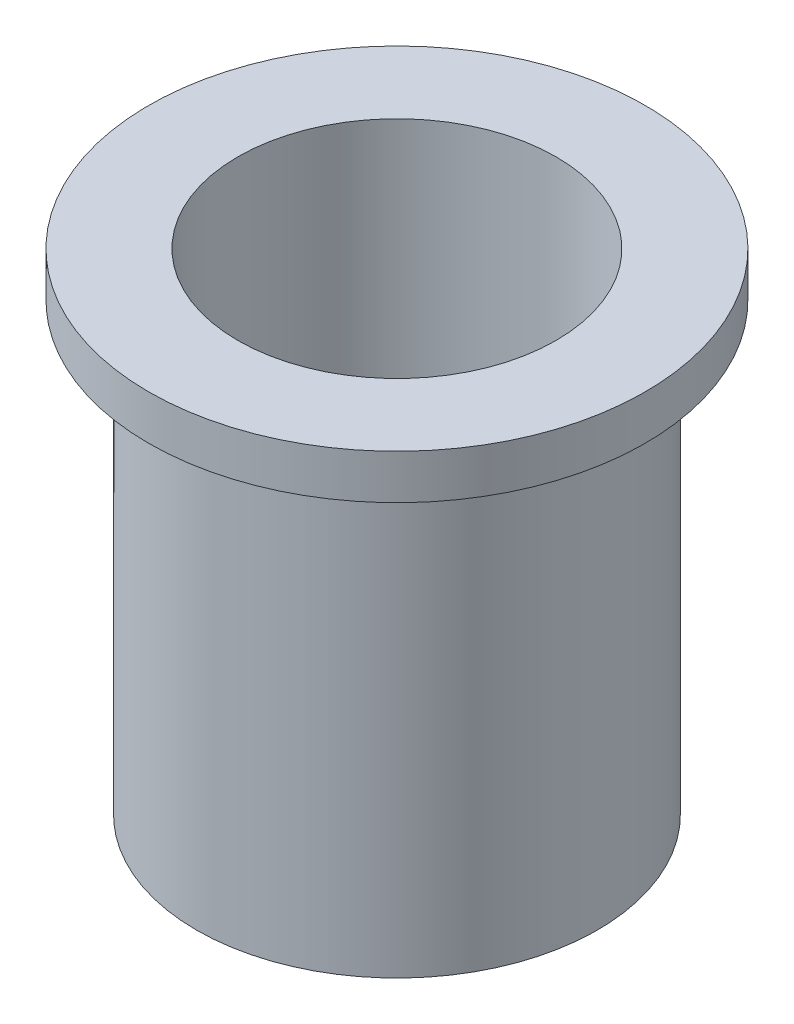
SolidWorks part; units mm, degrees
ref_plane "Front Plane" through (0, 0, 0) normal (0, 0, 1) x (1, 0, 0)
ref_plane "Top Plane" through (0, 0, 0) normal (0, 1, 0) x (1, 0, 0)
ref_plane "Right Plane" through (0, 0, 0) normal (1, 0, 0) x (0, 0, -1)
sketch "Sketch1" plane through (0, 0, 0) normal (0, 0, 1) x (1, 0, 0)
  line L0 (0, 24.9951) -> (0, -20.3242) construction
  line L1 (7.1438, -11) -> (7.1438, 11)
  line L2 (7.1438, 11) -> (11.1438, 11)
  line L3 (11.1438, 11) -> (11.1438, 9)
  line L4 (11.1438, 9) -> (9, 9)
  line L5 (9, 9) -> (9, -11)
  line L6 (9, -11) -> (7.1438, -11)
  point P9 (7.1438, 0)
  dimension "D1" = 7.1437
  dimension "D2" = 9
  dimension "D3" = 20
  dimension "D4" = 4
  dimension "D5" = 2
revolve "Revolve1" add sketch "Sketch1" angle 360 about L0
